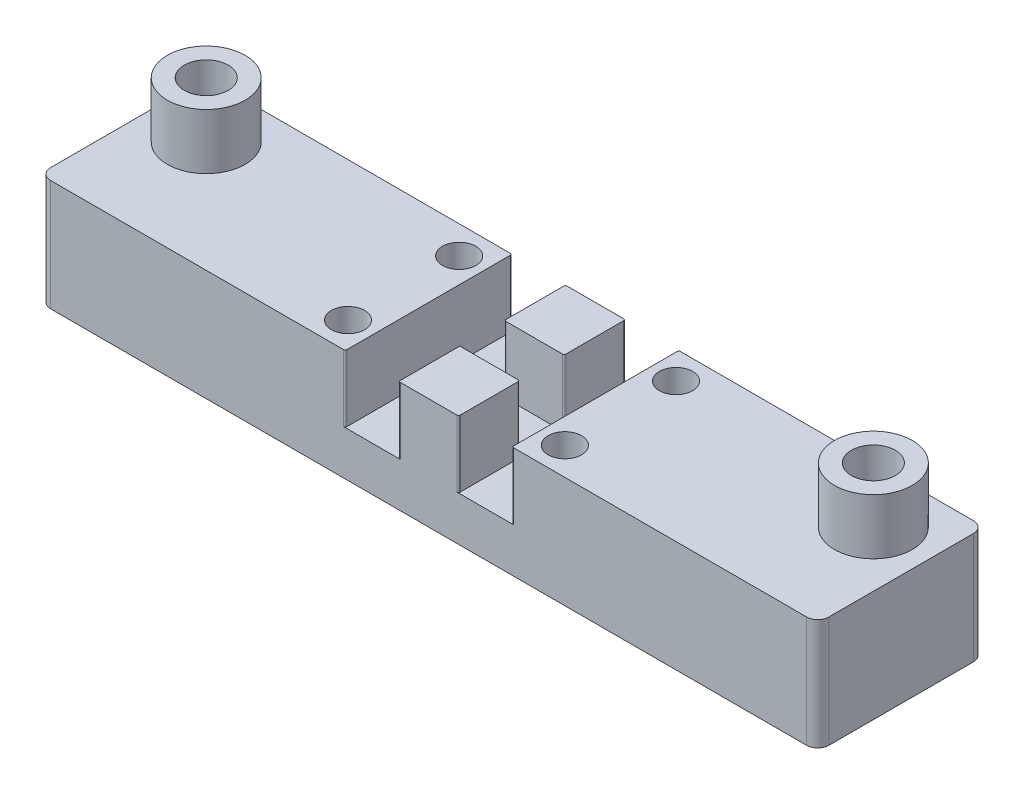
SolidWorks part; units mm, degrees
ref_plane "Front Plane" through (0, 0, 0) normal (0, 0, 1) x (1, 0, 0)
ref_plane "Top Plane" through (0, 0, 0) normal (0, 1, 0) x (1, 0, 0)
ref_plane "Right Plane" through (0, 0, 0) normal (1, 0, 0) x (0, 0, -1)
sketch "Sketch1" plane through (0, 0, 0) normal (0, 1, 0) x (1, 0, 0)
  line L0 (-1000, 0) -> (49000, 0) construction
  line L1 (0, -1000) -> (0, 49000) construction
  line L2 (0, 10) -> (70, 10) construction
  line L3 (0, 0) -> (70, 0)
  line L4 (0, 0) -> (0, 15)
  line L5 (0, 15) -> (70, 15)
  line L6 (70, 0) -> (70, 15)
  line L7 (35, 0) -> (35, 15) construction
  line L8 (26.75, 6.5711) -> (26.75, 2.5) construction
  line L9 (0, 7.5) -> (70, 7.5) construction
  line L10 (27.25, 15) -> (27.25, 0) construction
  line L11 (25.25, 12.5) -> (44.75, 12.5) construction
  line L12 (42.75, 10) -> (42.75, 0) construction
  circle A0 centre (5, 10) radius 1.75
  circle A1 centre (65, 10) radius 1.75
  circle A2 centre (25.25, 12.5) radius 1.5
  circle A3 centre (44.75, 12.5) radius 1.5
  circle A4 centre (44.75, 2.5) radius 1.5
  circle A5 centre (25.25, 2.5) radius 1.5
  point P29 (44.75, 2.5)
  point P30 (25.25, 2.5)
  dimension "D3" = 3.5
  dimension "D7" = 3
  dimension "D1" = 70
  dimension "D2" = 15
  dimension "D4" = 5
  dimension "D5" = 15.5
  dimension "D6" = 0.5
  dimension "D8" = 60
  dimension "D9" = 5
  dimension "D10" = 2.5
extrude "Boss-Extrude1" add sketch "Sketch1" along normal blind 10
sketch "Sketch2" plane through (0, 10, 0) normal (0, 1, 0) x (1, 0, 0)
  line L0 (70, 15) -> (0, 15) construction
  line L1 (27.5, 15) -> (42.5, 15)
  line L2 (27.5, 15) -> (27.5, 0)
  line L3 (27.5, 0) -> (42.5, 0)
  line L4 (42.5, 15) -> (42.5, 0)
  line L5 (0, 0) -> (70, 0) construction
  line L6 (35, 15) -> (35, 0) construction
  line L7 (0, 15) -> (0, 0) construction
  line L8 (70, 0) -> (70, 15) construction
  dimension "D1" = 15
extrude "Cut-Extrude1" cut sketch "Sketch2" against normal blind 6
sketch "Sketch3" plane through (0, 4, 0) normal (0, 1, 0) x (1, 0, 0)
  line L0 (42.5, 15) -> (27.5, 15) construction
  line L1 (32.3056, 15) -> (37.6944, 15)
  line L2 (32.3056, 15) -> (32.3056, 9.5)
  line L3 (32.3056, 9.5) -> (37.6944, 9.5)
  line L4 (37.6944, 15) -> (37.6944, 9.5)
  line L5 (35, 0) -> (35, 15) construction
  line L6 (27.5, 0) -> (42.5, 0) construction
  line L7 (27.5, 7.5) -> (42.5, 7.5) construction
  line L8 (27.5, 15) -> (27.5, 0) construction
  line L9 (42.5, 0) -> (42.5, 15) construction
  line L10 (37.6944, 0) -> (37.6944, 5.5)
  line L11 (32.3056, 5.5) -> (37.6944, 5.5)
  line L12 (32.3056, 0) -> (32.3056, 5.5)
  line L13 (32.3056, 0) -> (37.6944, 0)
  circle A0 centre (35, 12.25) radius 3.85 construction
  circle A1 centre (35, 2.75) radius 3.85 construction
  dimension "D1" = 7.7
  dimension "D2" = 5.3889
  dimension "D3" = 5.5
  dimension "D4" = 9.5
extrude "Boss-Extrude2" add sketch "Sketch3" along normal blind 6
fillet "Fillet1" radius 1 4 edges at (0, 5, -15) (70, 5, -15) (70, 5, 0) (0, 5, 0)
fillet "Fillet2" radius 0.15 11 edges at (27.5, 7, 0) (32.3056, 7, -15) (42.5, 7, -15) (37.6944, 7, -15) (42.5, 7, 0) (27.5, 7, -15) (32.3056, 7, -9.5) (37.6944, 7, -9.5) (37.6944, 7, -5.5) (37.6944, 7, 0) (32.3056, 7, 0)
sketch "Sketch4" plane through (0, 10, 0) normal (0, 1, 0) x (1, 0, 0)
  line L0 (35, 25.5941) -> (35, -23.2362) construction
  circle A0 centre (5, 10) radius 3.5
  circle A1 centre (5, 10) radius 1.75 construction
  circle A2 centre (5, 10) radius 1.75
  circle A3 centre (5, 10) radius 1.75 construction
  circle A4 centre (65, 10) radius 1.75 construction
  circle A5 centre (65, 10) radius 1.75
  circle A6 centre (65, 10) radius 3.5
  dimension "D1" = 7
extrude "Boss-Extrude3" add sketch "Sketch4" along normal offset from surface (5 mm away) 15 up to face at (44.75, 0, -1)
sketch "Sketch5" plane through (0, 15, 0) normal (0, 1, 0) x (1, 0, 0)
  circle A0 centre (5, 10) radius 1.85
  circle A1 centre (65, 10) radius 1.85
  dimension "D1" = 3.7
extrude "Cut-Extrude2" cut sketch "Sketch5" against normal through all
sketch "Sketch6" plane through (0, 15, 0) normal (0, 1, 0) x (1, 0, 0)
  circle A0 centre (5, 10) radius 1.975
  circle A1 centre (65, 10) radius 1.975
  dimension "D1" = 3.95
extrude "Cut-Extrude3" cut sketch "Sketch6" against normal blind 4
